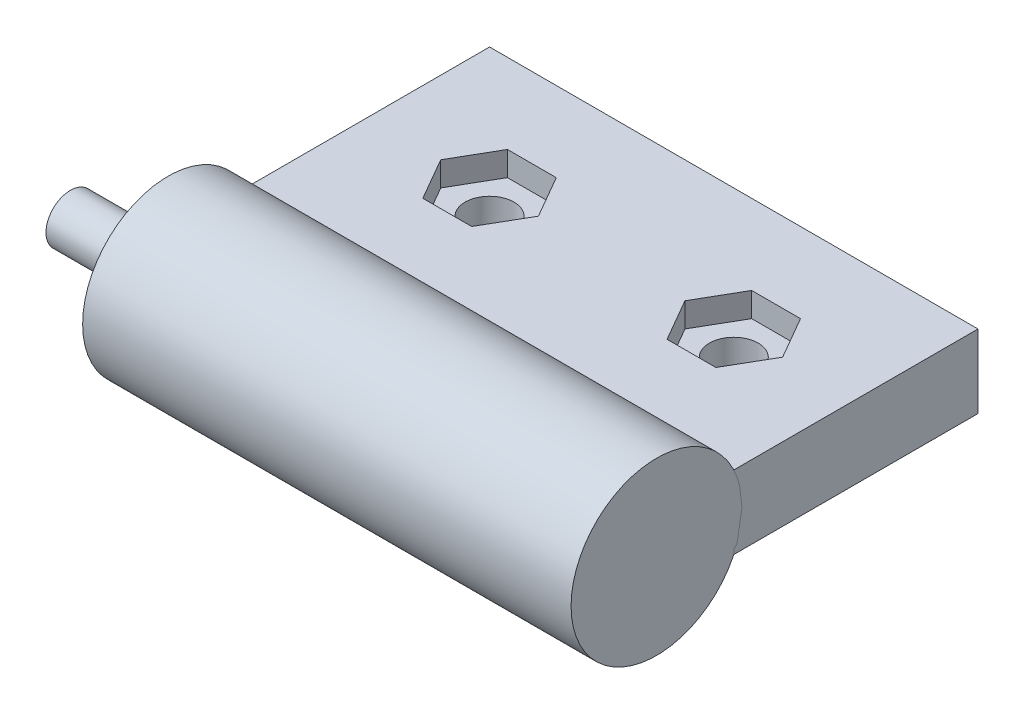
SolidWorks part; units mm, degrees
ref_plane "前视基准面" through (0, 0, 0) normal (0, 0, 1) x (1, 0, 0)
ref_plane "上视基准面" through (0, 0, 0) normal (0, 1, 0) x (1, 0, 0)
ref_plane "右视基准面" through (0, 0, 0) normal (1, 0, 0) x (0, 0, -1)
other "Configuration Table"
sketch "草图1" plane through (0, 0, 0) normal (0, 1, 0) x (1, 0, 0)
  line L0 (0, 2.5) -> (10, 2.5) construction
  line L1 (0, 0) -> (10, 0)
  line L2 (0, 0) -> (0, 5)
  line L3 (0, 5) -> (10, 5)
  line L4 (10, 0) -> (10, 5)
  circle A0 centre (2.5, 2.5) radius 0.5
  circle A1 centre (7.5, 2.5) radius 0.5
  point P11 (0, 0)
  point P12 (0, 0)
  dimension "D3" = 1
  dimension "D4" = 1
  dimension "D1" = 10
  dimension "D2" = 5
  dimension "D5" = 2.5
  dimension "D6" = 2.5
extrude "凸台-拉伸1" add sketch "草图1" along normal blind 1
sketch "草图2" plane through (0, 1, 0) normal (0, 1, 0) x (1, 0, 0)
  line L0 (5, 5) -> (5, 0) construction
  line L1 (10, 5) -> (0, 5) construction
  line L2 (0, 0) -> (10, 0) construction
  line L3 (0, 2.5) -> (5, 2.5) construction
  line L4 (0, 5) -> (0, 0) construction
  line L5 (0, 5) -> (5, 5)
  line L6 (2.5, 5) -> (2.5, 0) construction
  line L7 (3, 3.366) -> (2, 3.366)
  line L8 (3, 3.366) -> (3.5, 2.5)
  line L9 (2, 3.366) -> (1.5, 2.5)
  line L10 (3, 1.634) -> (3.5, 2.5)
  line L11 (3, 1.634) -> (2, 1.634)
  line L12 (2, 1.634) -> (1.5, 2.5)
  line L13 (7, 3.366) -> (6.5, 2.5)
  line L14 (7, 1.634) -> (6.5, 2.5)
  line L15 (7, 1.634) -> (8, 1.634)
  line L16 (8, 1.634) -> (8.5, 2.5)
  line L17 (8, 3.366) -> (8.5, 2.5)
  line L18 (7, 3.366) -> (8, 3.366)
  point P19 (2.5, 3.366)
  point P23 (2.8996, 3.4697)
  line M10 (0, 5) -> (0, 0)
  line M11 (0, 0) -> (10, 0)
  line M12 (10, 0) -> (10, 5)
  line M13 (10, 5) -> (0, 5)
  dimension "D1" = 60
  dimension "D2" = 0.5
  dimension "D3" = 1
extrude "凸台-拉伸2" add sketch "草图2" along normal blind 0.5 contours L11 L12 L9 L7 L8 L10 L13 L18 L17 L16 L15 L14 M13 M10 M11 M12
sketch "草图3" plane through (10, 0, 0) normal (1, 0, 0) x (0, 0, -1)
  line L0 (5, 0.75) -> (0, 0.75) construction
  line L6 (5, 1.5) -> (5, 0)
  circle A0 centre (-1.5811, 0.75) radius 1.75
  point P8 (5, 0.75)
  point P11 (0, 0)
  dimension "D1" = 3.5
extrude "凸台-拉伸3" add sketch "草图3" against normal up to surface (10 mm away) separate body contours A0 up to face at (0, 0.75, -2.5)
sketch "草图5" plane through (0, 0, 0) normal (-1, 0, 0) x (0, 0, 1)
  circle A0 centre (1.5811, 0.75) radius 0.5
  dimension "D1" = 1
extrude "凸台-拉伸4" add sketch "草图5" along normal blind 2
